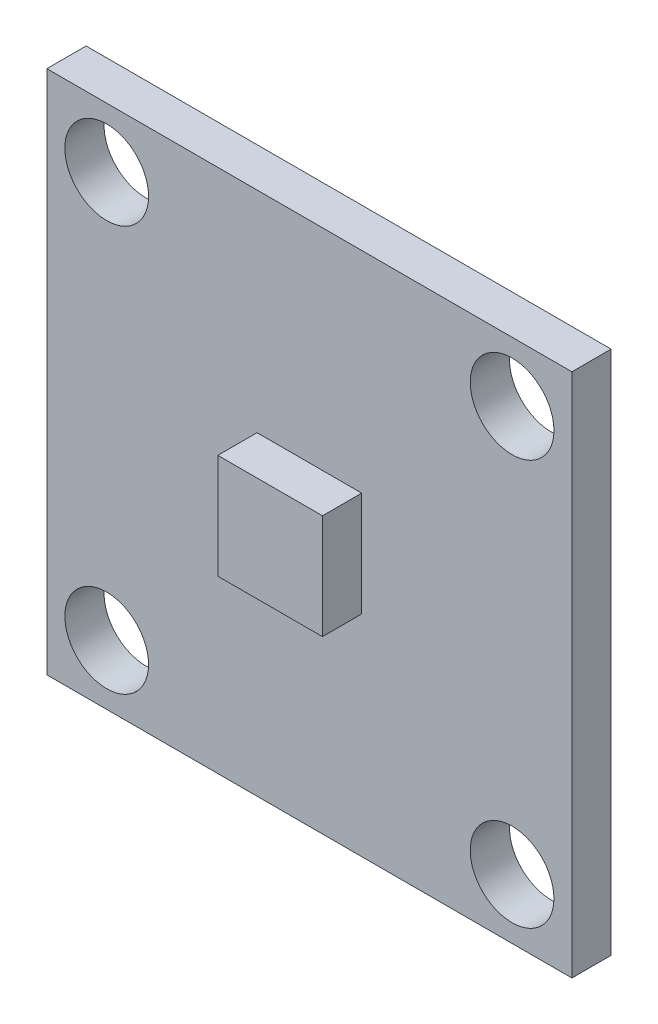
SolidWorks part; units mm, degrees
material "E-玻璃纤维"
ref_plane "前视基准面" through (0, 0, 0) normal (0, 0, 1) x (1, 0, 0)
ref_plane "上视基准面" through (0, 0, 0) normal (0, 1, 0) x (1, 0, 0)
ref_plane "右视基准面" through (0, 0, 0) normal (1, 0, 0) x (0, 0, -1)
sketch "草图1" plane through (0, 0, 0) normal (0, 0, 1) x (1, 0, 0)
  line L1 (-10.033, 10.033) -> (10.033, 10.033)
  line L2 (-10.033, 10.033) -> (-10.033, -10.033)
  line L3 (-10.033, -10.033) -> (10.033, -10.033)
  line L4 (10.033, 10.033) -> (10.033, -10.033)
  circle A0 centre (-7.747, 7.747) radius 1.6
  circle A1 centre (7.747, 7.747) radius 1.6
  circle A2 centre (-7.747, -7.747) radius 1.6
  circle A3 centre (7.747, -7.747) radius 1.6
  point P4 (0, 10.033)
  point P6 (-10.033, 0)
  dimension "D6" = 3.2
  dimension "D1" = 20.066
  dimension "D2" = 2.286
  dimension "D3" = 2.286
  dimension "D4" = 2.286
  dimension "D5" = 2.286
extrude "凸台-拉伸1" add sketch "草图1" along normal blind 1.5
sketch "草图2" plane through (0, 0, 1.5) normal (0, 0, 1) x (1, 0, 0)
  line L1 (-2, 2) -> (2, 2)
  line L2 (-2, 2) -> (-2, -2)
  line L3 (-2, -2) -> (2, -2)
  line L4 (2, 2) -> (2, -2)
  point P4 (0, 2)
  point P6 (-2, 0)
  dimension "D1" = 4
extrude "凸台-拉伸2" add sketch "草图2" along normal blind 1.5
